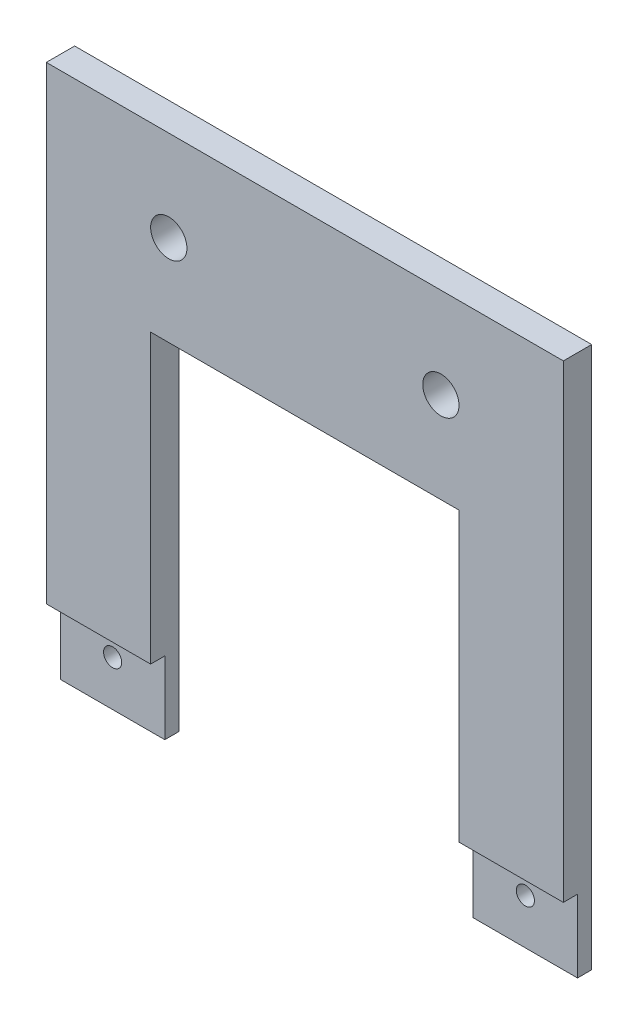
SolidWorks part; units mm, degrees
ref_plane "Front Plane" through (0, 0, 0) normal (0, 0, 1) x (1, 0, 0)
ref_plane "Top Plane" through (0, 0, 0) normal (0, 1, 0) x (1, 0, 0)
ref_plane "Right Plane" through (0, 0, 0) normal (1, 0, 0) x (0, 0, -1)
sketch "Sketch1" plane through (0, 0, 0) normal (0, 0, 1) x (1, 0, 0)
  line L0 (-8.5, -19.85) -> (-8.5, 0)
  line L3 (14.25, 10) -> (-14.25, 10)
  line L4 (-14.25, -19.85) -> (-14.25, 10)
  line L5 (-8.5, 0) -> (8.5, 0)
  line L6 (-14.25, -19.85) -> (-8.5, -19.85)
  line L7 (-8.5, 0) -> (8.5, 0)
  line L8 (0, 10) -> (0, 0)
  line L9 (0, -16.85) -> (0, -17.85)
  line L10 (-8.5, 4) -> (-6.5, 4)
  line L11 (-8.5, 4) -> (-8.5, 6)
  line L12 (-8.5, 6) -> (-6.5, 6)
  line L13 (-6.5, 4) -> (-6.5, 6)
  line L14 (-8.5, 4) -> (-6.5, 6) construction
  line L15 (-8.5, 6) -> (-6.5, 4) construction
  line L20 (8.5, 6) -> (6.5, 4) construction
  line L21 (8.5, 4) -> (6.5, 6) construction
  line L26 (6.5, 4) -> (6.5, 6)
  line L27 (8.5, 6) -> (6.5, 6)
  line L28 (8.5, 4) -> (8.5, 6)
  line L29 (8.5, 4) -> (6.5, 4)
  line L31 (14.25, -19.85) -> (8.5, -19.85)
  line L32 (14.25, -19.85) -> (14.25, 10)
  line L33 (8.5, -19.85) -> (8.5, 0)
  circle A0 centre (-7.5, 5) radius 1
  circle A3 centre (7.5, 5) radius 1
  circle A4 centre (-11.375, -17.35) radius 0.5
  circle A6 centre (11.375, -17.35) radius 0.5
  point P18 (-11.375, -16.85)
  point P19 (-11.375, -16.85)
  point P20 (0, -16.85)
  point P25 (-11.375, -17.85)
  dimension "D5" = 2
  dimension "D10" = 2.5
  dimension "D8" = 1
  dimension "D11" = 2.875
  dimension "D1" = 29.85
  dimension "D2" = 14.25
  dimension "D3" = 10
  dimension "D4" = 5.75
  dimension "D6" = 4
  dimension "D7" = 5.75
extrude "Boss-Extrude1" add sketch "Sketch1" along normal mid plane 1.5625
sketch "Sketch2" plane through (0, 0, 0.7813) normal (0, 0, 1) x (1, 0, 0)
  line L0 (-8.5, -19.85) -> (-8.5, 0) construction
  line L1 (-14.25, -19.85) -> (-8.5, -19.85)
  line L2 (-14.25, -19.85) -> (-14.25, -15.85)
  line L3 (-14.25, -15.85) -> (-8.5, -15.85)
  line L4 (-8.5, -19.85) -> (-8.5, -15.85)
  line L5 (0, -15.85) -> (0, -19.85)
  line L6 (14.25, -15.85) -> (8.5, -15.85)
  line L7 (8.5, -19.85) -> (8.5, -15.85)
  line L8 (14.25, -19.85) -> (8.5, -19.85)
  line L9 (14.25, -19.85) -> (14.25, -15.85)
  dimension "D1" = 4
extrude "Cut-Extrude1" cut sketch "Sketch2" against normal blind 0.7813
